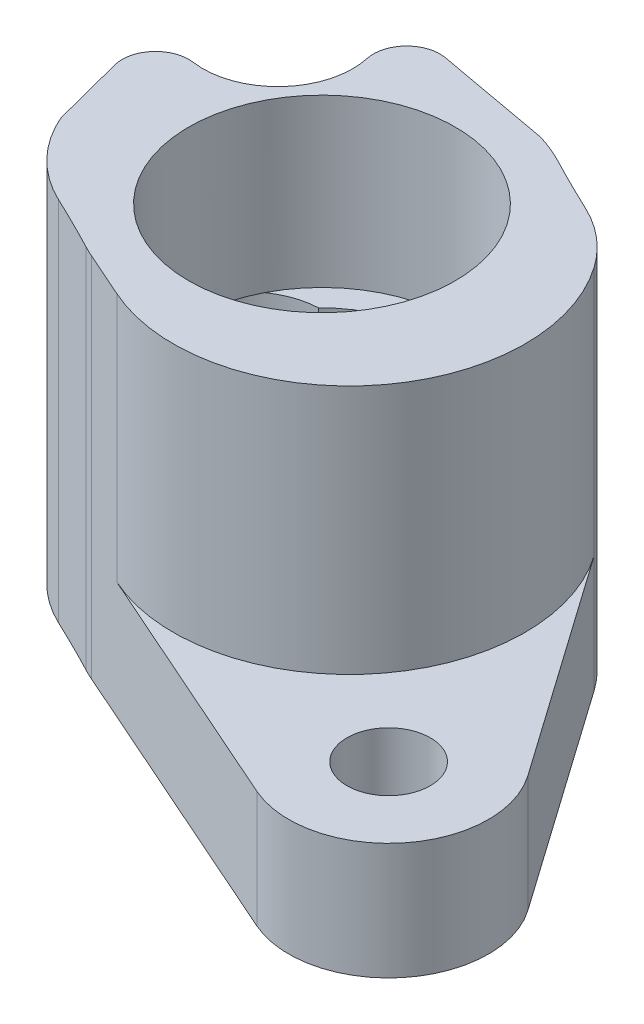
SolidWorks part; units mm, degrees
ref_plane "Front Plane" through (0, 0, 0) normal (0, 0, 1) x (1, 0, 0)
ref_plane "Top Plane" through (0, 0, 0) normal (0, 1, 0) x (1, 0, 0)
ref_plane "Right Plane" through (0, 0, 0) normal (1, 0, 0) x (0, 0, -1)
sketch "Sketch2" plane through (0, 0, 0) normal (0, 1, 0) x (1, 0, 0)
  line L0 (-4.5, 0) -> (4.5, 0) construction
  line L1 (0, 0) -> (0, 6.5) construction
  line L2 (0, -6.5) -> (0, -10.5) construction
  line L5 (-4.2485, -9.6021) -> (13.5723, -17.4869)
  line L8 (11.4517, 4.8912) -> (20.9071, -8.5474)
  line L9 (10, -12) -> (16, -12) construction
  line L10 (-9, 0) -> (-10.6043, 0) construction
  line L11 (0, 6.5) -> (0, 7.9533) construction
  line L12 (16, -12) -> (0, 0) construction
  line L13 (0, 0) -> (-18.9313, 14.1985) construction
  line L14 (0, 0) -> (-11.5651, 8.6738) construction
  line L15 (0, 7.9533) -> (-10.6043, 7.9533) construction
  line L16 (-10.6043, 7.9533) -> (-10.6043, 0) construction
  line L17 (-16.1478, 5.5692) -> (-12.3085, -3.3581)
  line L18 (-8.8217, 13.7183) -> (3.1018, 10.0314)
  arc A0 (-4.6944, -4.4958) -> (4.6944, -4.4958) centre (0, 0) ccw
  arc A1 (4.6944, -4.4958) -> (4.6944, 4.4958) centre (4.5, 0) ccw
  arc A2 (-4.6944, -4.4958) -> (-4.6944, 4.4958) centre (-4.5, 0) cw
  arc A3 (4.6944, 4.4958) -> (-4.6944, 4.4958) centre (0, 0) ccw
  arc A4 (11.4517, 4.8912) -> (6.4722, 8.268) centre (4.5, 0) ccw
  arc A5 (6.4722, 8.268) -> (3.1018, 10.0314) centre (0, 0) ccw
  arc A6 (-6.4722, -8.268) -> (-12.3085, -3.3581) centre (-4.5, 0) cw
  arc A7 (-6.4722, -8.268) -> (-4.2485, -9.6021) centre (0, 0) ccw
  circle A8 centre (16, -12) radius 2.5
  arc A9 (13.5723, -17.4869) -> (20.9071, -8.5474) centre (16, -12) ccw
  arc A11 (6.4722, -8.268) -> (6.4722, 8.268) centre (4.5, 0) ccw construction
  arc A12 (-6.4722, -8.268) -> (6.4722, -8.268) centre (0, 0) ccw construction
  circle A13 centre (-10.6043, 7.9533) radius 2.5
  arc A14 (-5.7939, 4.31) -> (-5.7768, 4.3326) centre (-10.6043, 7.9533) ccw
  arc A15 (-8.8217, 13.7183) -> (-16.1478, 5.5692) centre (-10.6043, 7.9533) ccw
  arc A16 (6.4722, 8.268) -> (-6.4722, 8.268) centre (0, 0) ccw construction
  arc A17 (-6.4722, -8.268) -> (-6.4722, 8.268) centre (-4.5, 0) cw construction
  point P6 (0, 0)
  dimension "D1" = 13
  dimension "D3" = 4
  dimension "D4" = 12
  dimension "D5" = 5
  dimension "D2" = 9
extrude "Boss-Extrude1" add sketch "Sketch2" along normal blind 7
fillet "Fillet1" radius 90 2 edges at (-6.4722, 3.5, 8.268) (6.4722, 3.5, -8.268)
sketch "Sketch3" plane through (0, 7, 0) normal (0, 1, 0) x (1, 0, 0)
  line L2 (-13.4469, 1.0128) -> (-12.3085, -3.3581)
  line L4 (-4.2485, -9.6021) -> (13.5723, -17.4869) construction
  line L5 (-4.2485, -9.6021) -> (-1.4542, -10.8384)
  line L6 (-3.8952, 11.3055) -> (3.1018, 10.0314)
  arc A0 (4.6944, -4.4958) -> (4.6944, 4.4958) centre (4.5, 0) ccw construction
  arc A1 (-4.6944, -4.4958) -> (4.6944, -4.4958) centre (0, 0) ccw construction
  arc A2 (-4.6944, 4.4958) -> (-4.6944, -4.4958) centre (-4.5, 0) ccw construction
  arc A3 (4.6944, 4.4958) -> (-4.6944, 4.4958) centre (0, 0) ccw construction
  arc A4 (4.6944, -4.4958) -> (4.6944, 4.4958) centre (4.5, 0) ccw
  arc A5 (-4.6944, -4.4958) -> (4.6944, -4.4958) centre (0, 0) ccw
  arc A6 (-4.6944, 4.4958) -> (-4.6944, -4.4958) centre (-4.5, 0) ccw
  arc A7 (4.6944, 4.4958) -> (-4.6944, 4.4958) centre (0, 0) ccw
  arc A9 (-6.0278, 7.3427) -> (-6.1496, 7.3163) centre (-4.5, 0) ccw
  arc A14 (-6.0278, 7.3427) -> (-6.0278, -7.3427) centre (-4.5, 0) ccw construction
  arc A15 (6.0278, 7.3427) -> (-6.0278, 7.3427) centre (0, 0) ccw construction
  arc A16 (6.0278, -7.3427) -> (6.0278, 7.3427) centre (4.5, 0) ccw construction
  arc A17 (-6.0278, -7.3427) -> (6.0278, -7.3427) centre (0, 0) ccw construction
  arc A18 (-11.2323, 3.4973) -> (-6.2076, 8.9118) centre (-10.6043, 7.9533) ccw
  arc A19 (4.8553, 9.31) -> (3.1018, 10.0314) centre (0, 0) ccw construction
  arc A20 (4.8553, 9.31) -> (8.122, 7.6897) centre (46.4722, 89.1099) ccw construction
  arc A21 (11.4517, 4.8912) -> (8.122, 7.6897) centre (4.5, 0) ccw construction
  arc A22 (-4.8553, -9.31) -> (-8.122, -7.6897) centre (-46.4722, -89.1099) ccw construction
  arc A23 (-12.3085, -3.3581) -> (-8.122, -7.6897) centre (-4.5, 0) ccw construction
  arc A24 (4.8553, 9.31) -> (3.1018, 10.0314) centre (0, 0) ccw
  arc A25 (4.8553, 9.31) -> (8.122, 7.6897) centre (46.4722, 89.1099) ccw
  arc A26 (11.4517, 4.8912) -> (8.122, 7.6897) centre (4.5, 0) ccw
  arc A27 (-4.8553, -9.31) -> (-8.122, -7.6897) centre (-46.4722, -89.1099) ccw
  arc A28 (-12.3085, -3.3581) -> (-8.122, -7.6897) centre (-4.5, 0) ccw
  arc A29 (-4.8553, -9.31) -> (-4.2485, -9.6021) centre (0, 0) ccw construction
  arc A30 (-4.8553, -9.31) -> (-4.2485, -9.6021) centre (0, 0) ccw
  arc A31 (-1.4542, -10.8384) -> (11.4517, 4.8912) centre (2.8174, -1.1839) ccw
  arc A32 (-3.8952, 11.3055) -> (-6.2076, 8.9118) centre (-4.2535, 9.3379) ccw
  arc A33 (-13.4469, 1.0128) -> (-11.2323, 3.4973) centre (-11.5114, 1.5169) cw
  dimension "D2" = 2
  dimension "D1" = 3
extrude "Boss-Extrude3" add sketch "Sketch3" along normal blind 15
sketch "Sketch4" plane through (0, 22, 0) normal (0, 1, 0) x (1, 0, 0)
  circle A0 centre (0, 0) radius 8
  dimension "D1" = 16
extrude "Cut-Extrude1" cut sketch "Sketch4" against normal blind 10
sketch "Sketch5" plane through (0, 12, 0) normal (0, 1, 0) x (1, 0, 0)
  arc A0 (-7.1111, 3.665) -> (-7.1111, -3.665) centre (0, 0) ccw
  arc A1 (-7.1111, 3.665) -> (-7.1111, -3.665) centre (-4.5, 0) ccw construction
  arc A2 (-7.1111, 3.665) -> (-7.1111, -3.665) centre (-4.5, 0) ccw
  arc A3 (7.1111, -3.665) -> (7.1111, 3.665) centre (4.5, 0) ccw construction
  arc A4 (7.1111, -3.665) -> (7.1111, 3.665) centre (4.5, 0) ccw
  arc A5 (7.1111, -3.665) -> (7.1111, 3.665) centre (0, 0) ccw
extrude "Boss-Extrude4" add sketch "Sketch5" along normal up to surface (10 mm away) up to face at (0, 22, 0)
